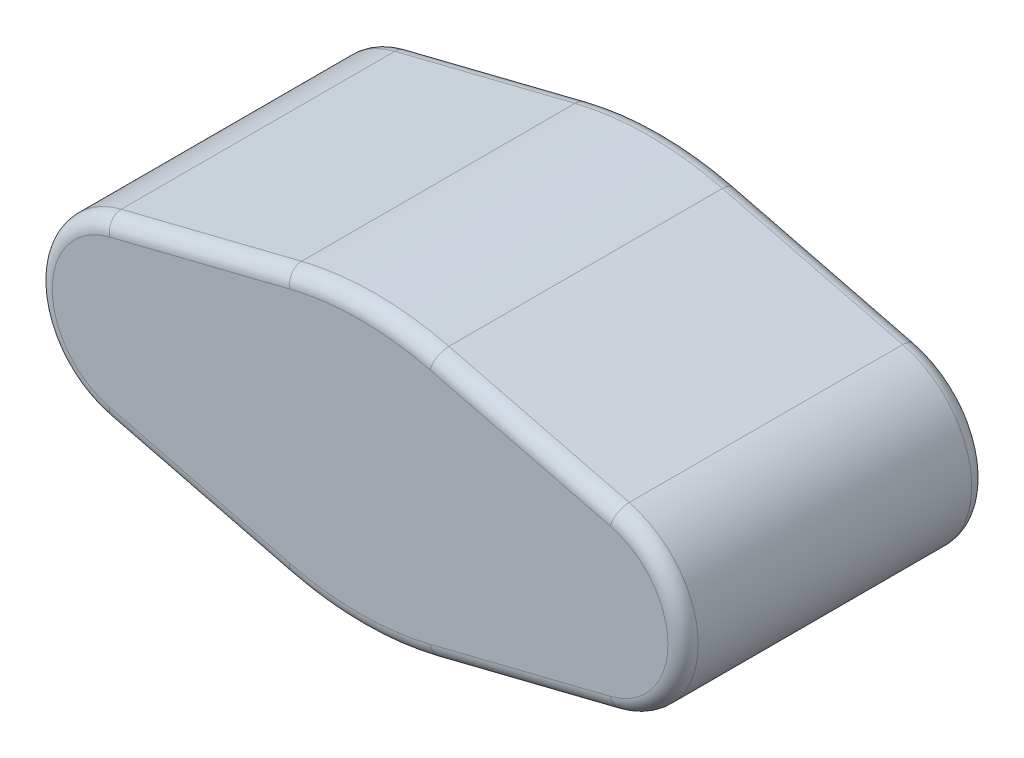
SolidWorks part; units mm, degrees
ref_plane "Спереди" through (0, 0, 0) normal (0, 0, 1) x (1, 0, 0)
ref_plane "Сверху" through (0, 0, 0) normal (0, 1, 0) x (1, 0, 0)
ref_plane "Справа" through (0, 0, 0) normal (1, 0, 0) x (0, 0, -1)
sketch "Эскиз1" plane through (0, 0, 0) normal (0, 0, 1) x (1, 0, 0)
  line L0 (0, 0) -> (-20, -5)
  line L1 (-20, -5) -> (0, -10)
  line L2 (0, -10) -> (20, -5)
  line L3 (20, -5) -> (0, 0)
  dimension "D1" = 40
  dimension "D2" = 10
extrude "Бобышка-Вытянуть1" add sketch "Эскиз1" along normal blind 10
fillet "Скругление1" radius 10 2 edges at (0, -10, 5) (0, 0, 5)
fillet "Скругление2" radius 3 2 edges at (20, -5, 5) (-20, -5, 5)
sketch "Эскиз2" plane through (0, 0, 0) normal (0, 0, -1) x (-1, 0, 0)
  line L0 (0, -0.3078) -> (0, -9.6922) construction
  arc A0 (2.4254, -0.6063) -> (-2.4254, -0.6063) centre (0, -10.3078) ccw construction
  arc A1 (-2.4254, -9.3937) -> (2.4254, -9.3937) centre (0, 0.3078) ccw construction
  circle A2 centre (0, -5) radius 3
  dimension "D1" = 6
extrude "Бобышка-Вытянуть2" add sketch "Эскиз2" along normal blind 1
fillet "Скругление3" radius 0.5 16 edges at (10.6307, -5, 0) (5.3918, -8.652, 0) (0, -9.6922, 0) (-5.3918, -8.652, 0) (-10.6307, -5, 0) (-5.3918, -1.348, 0) (0, -0.3078, 0) (10.6307, -5, 10) (5.3918, -8.652, 10) (0, -9.6922, 10) (-5.3918, -8.652, 10) (-10.6307, -5, 10) (-5.3918, -1.348, 10) (0, -0.3078, 10) (5.3918, -1.348, 0) (5.3918, -1.348, 10)
